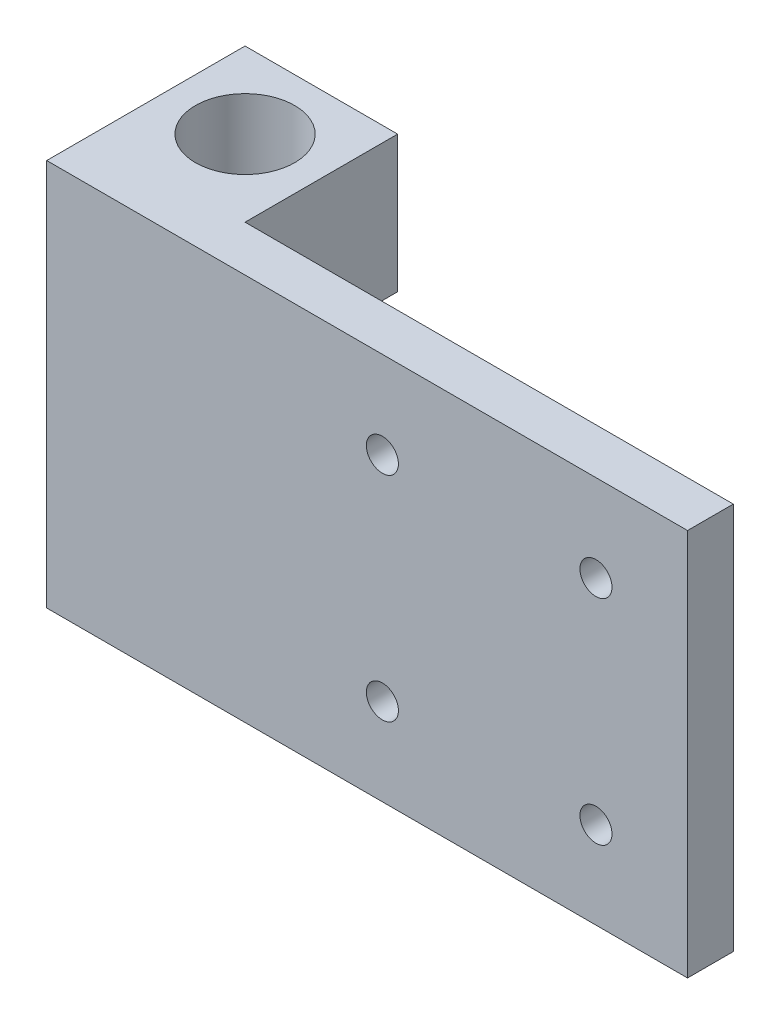
SolidWorks part; units mm, degrees
ref_plane "Front Plane" through (0, 0, 0) normal (0, 0, 1) x (1, 0, 0)
ref_plane "Top Plane" through (0, 0, 0) normal (0, 1, 0) x (1, 0, 0)
ref_plane "Right Plane" through (0, 0, 0) normal (1, 0, 0) x (0, 0, -1)
sketch "Sketch1" plane through (0, 0, 0) normal (0, 0, 1) x (1, 0, 0)
  line L1 (0, 0) -> (84, 0)
  line L2 (0, 0) -> (0, 50.8)
  line L3 (0, 50.8) -> (84, 50.8)
  line L4 (84, 0) -> (84, 50.8)
  circle A0 centre (72, 39.4) radius 2.1
  circle A1 centre (72, 11.4) radius 2.1
  circle A2 centre (44, 39.4) radius 2.1
  circle A3 centre (44, 11.4) radius 2.1
  dimension "D4" = 4.2
  dimension "D5" = 4.2
  dimension "D8" = 4.2
  dimension "D9" = 4.2
  dimension "D1" = 50.8
  dimension "D2" = 84
  dimension "D3" = 12
  dimension "D6" = 28
  dimension "D7" = 11.4
  dimension "D10" = 28
  dimension "D11" = 11.4
  dimension "D12" = 28
extrude "Boss-Extrude1" add sketch "Sketch1" along normal blind 6
sketch "Sketch3" plane through (0, 0, 0) normal (0, 0, -1) x (-1, 0, 0)
  line L0 (-84, 0) -> (-84, 50.8) construction
  line L1 (-20, 50.8) -> (0, 50.8)
  line L2 (-20, 50.8) -> (-20, 0)
  line L3 (-20, 0) -> (0, 0)
  line L4 (0, 50.8) -> (0, 0)
  line L5 (-84, 50.8) -> (0, 50.8) construction
  line L6 (0, 0) -> (-84, 0) construction
  dimension "D1" = 20
  dimension "D2" = 64
  dimension "D3" = 0
  dimension "D4" = 0
extrude "Boss-Extrude2" add sketch "Sketch3" along normal blind 20
sketch "Sketch5" plane through (0, 50.8, 0) normal (0, 1, 0) x (1, 0, 0)
  line L0 (20, 20) -> (20, 0) construction
  line L1 (0, 20) -> (20, 20) construction
  circle A0 centre (10, 10) radius 6.5
  dimension "D1" = 13
  dimension "D2" = 10
  dimension "D3" = 10
extrude "Cut-Extrude1" cut sketch "Sketch5" against normal blind 10
sketch "Sketch6" plane through (0, 0, 0) normal (0, -1, 0) x (1, 0, 0)
  line L0 (20, -20) -> (20, 0) construction
  line L1 (20, -20) -> (0, -20) construction
  circle A0 centre (10, -10) radius 6.5
  dimension "D1" = 13
  dimension "D2" = 10
  dimension "D3" = 10
extrude "Cut-Extrude2" cut sketch "Sketch6" against normal blind 10
sketch "Sketch7" plane through (0, 0, -20) normal (0, 0, -1) x (-1, 0, 0)
  line L0 (-20, 50.8) -> (-20, 0) construction
  line L1 (-10, 32.9) -> (-20, 32.9)
  line L2 (-10, 32.9) -> (-10, 17.9)
  line L3 (-10, 17.9) -> (-20, 17.9)
  line L4 (-20, 32.9) -> (-20, 17.9)
  line L6 (-20, 0) -> (0, 0) construction
  dimension "D1" = 10
  dimension "D2" = 15
  dimension "D3" = 17.9
extrude "Cut-Extrude3" cut sketch "Sketch7" against normal blind 10
equation "\"D5@Sketch1\"=\"D4@Sketch1\""
equation "\"D8@Sketch1\"=\"D4@Sketch1\""
equation "\"D9@Sketch1\"=\"D4@Sketch1\""
equation "\"D10@Sketch1\"=\"D6@Sketch1\""
equation "\"D11@Sketch1\"=\"D7@Sketch1\""
